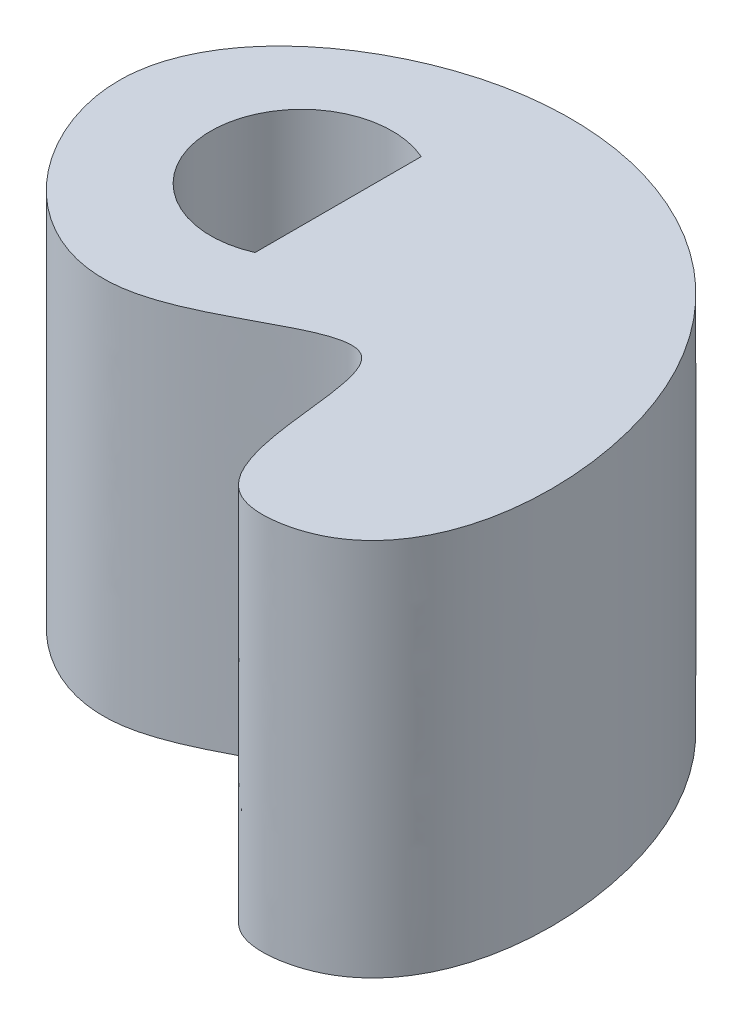
SolidWorks part; units mm, degrees
ref_plane "Front Plane" through (0, 0, 0) normal (0, 0, 1) x (1, 0, 0)
ref_plane "Top Plane" through (0, 0, 0) normal (0, 1, 0) x (1, 0, 0)
ref_plane "Right Plane" through (0, 0, 0) normal (1, 0, 0) x (0, 0, -1)
sketch "Sketch1" plane through (0, 0, 0) normal (0, 1, 0) x (1, 0, 0)
  line L0 (0.6092, 1.3817) -> (0.6092, -1.3817)
  arc A0 (0.6092, 1.3817) -> (0.6092, -1.3817) centre (0, 0) ccw
  spline S0 degree 3 poles (-0.5614, -4.5365) (-4.4337, 0.313) (0.7838, 4.3971) (6.9093, 1.5409) (6.6778, -4.954) (3.0264, -5.2346) (3.8309, -0.3014) (-0.5614, -4.5365) (-4.4337, 0.313) (0.7838, 4.3971) knots -0.382633 -0.268128 -0.153624 0 0.153624 0.396525 0.581158 0.617367 0.731872 0.846376 1 1.153624 1.396525 1.581158 only from (-3, 0) to (-3, 0)
  point P1 (0, 0)
  point P7 (0, 0)
  point P9 (0, 0)
  point P10 (0, 0)
  point P12 (0, 0)
  point P14 (0, 0)
extrude "Boss-Extrude1" add sketch "Sketch1" along normal blind 6.3
